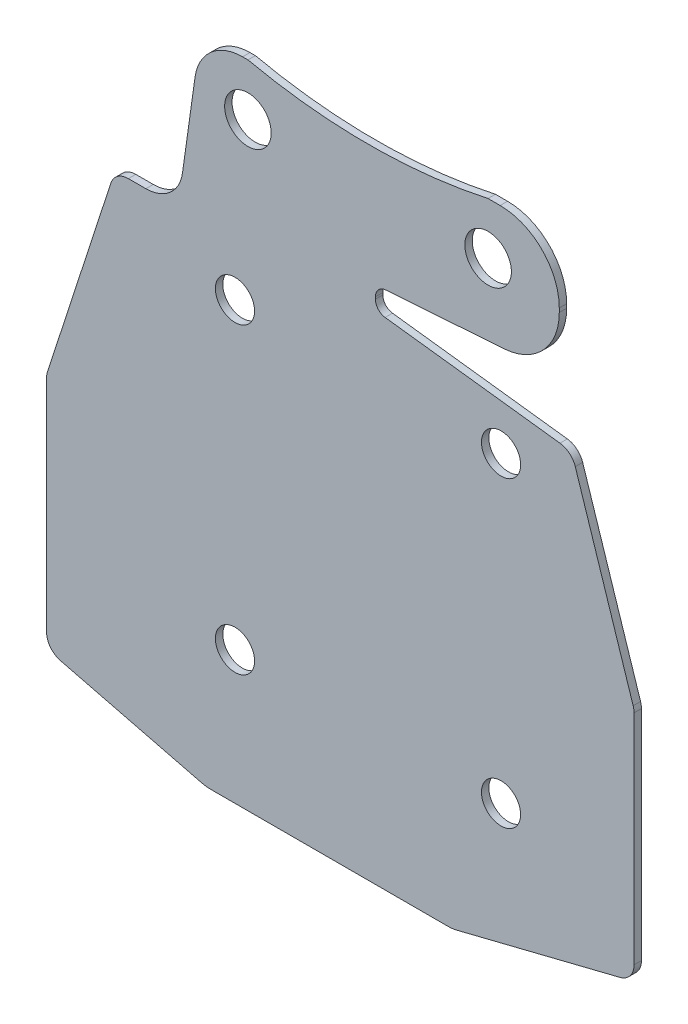
SolidWorks part; units mm, degrees
ref_plane "Plano frontal" through (0, 0, 0) normal (0, 0, 1) x (1, 0, 0)
ref_plane "Plano superior" through (0, 0, 0) normal (0, 1, 0) x (1, 0, 0)
ref_plane "Plano direito" through (0, 0, 0) normal (1, 0, 0) x (0, 0, -1)
sketch "Esboço1" plane through (0, 0, 0) normal (0, 0, 1) x (1, 0, 0)
  line L0 (-28.901, -44.5642) -> (-50.4937, -39.1805)
  line L1 (-50.4937, -39.1805) -> (-50.4937, -7.0642)
  line L2 (-50.4937, -7.0642) -> (-41.2335, 21.4358)
  line L3 (-41.2335, 21.4358) -> (-32.7051, 21.4358)
  line L4 (-32.7051, 21.4358) -> (-29.6132, 43.4358)
  line L5 (-29.6132, 43.4358) -> (18.8868, 43.4358)
  line L6 (18.8868, 43.4358) -> (18.8868, 27.4358)
  line L7 (18.8868, 27.4358) -> (-5.9937, 25.696)
  line L8 (-5.9937, 25.696) -> (-5.9937, 22.696)
  line L9 (-5.9937, 22.696) -> (20.5584, 19.4358)
  line L10 (20.5584, 19.4358) -> (29.0063, -6.5642)
  line L11 (29.0063, -6.5642) -> (29.0063, -38.4375)
  line L12 (29.0063, -38.4375) -> (4.4333, -44.5642)
  line L13 (4.4333, -44.5642) -> (-28.901, -44.5642)
  dimension "D1" = 14
  dimension "D2" = 14
  dimension "D3" = 79.5
  dimension "D4" = 18
  dimension "D5" = 18
  dimension "D6" = 8
  dimension "D7" = 66
  dimension "D8" = 37.5
  dimension "D9" = 22
  dimension "D10" = 11
  dimension "D11" = 4
  dimension "D12" = 24
  dimension "D13" = 48.5
  dimension "D14" = 38
  dimension "D15" = 35
  dimension "D16" = 16
  dimension "D17" = 3
extrude "Ressalto-extrusão1" add sketch "Esboço1" along normal blind 1
fillet "Filete1" radius 5 1 edges at (-32.7051, 21.4358, 0.5)
fillet "Filete2" radius 6.5 1 edges at (-29.6132, 43.4358, 0.5)
fillet "Filete3" radius 8 2 edges at (18.8868, 27.4358, 0.5) (18.8868, 43.4358, 0.5)
fillet "Filete4" radius 1.5 2 edges at (-5.9937, 22.696, 0.5) (-5.9937, 25.696, 0.5)
fillet "Filete5" radius 2.5 1 edges at (20.5584, 19.4358, 0.5)
fillet "Filete6" radius 2.5 1 edges at (29.0063, -6.5642, 0.5)
fillet "Filete7" radius 2.5 1 edges at (29.0063, -38.4375, 0.5)
fillet "Filete9" radius 5 2 edges at (4.4333, -44.5642, 0.5) (-28.901, -44.5642, 0.5)
fillet "Filete10" radius 2.5 2 edges at (-50.4937, -7.0642, 0.5) (-50.4937, -39.1805, 0.5)
fillet "Filete11" radius 2.5 1 edges at (-41.2335, 21.4358, 0.5)
sketch "Esboço2" plane through (0, 0, 1) normal (0, 0, 1) x (1, 0, 0)
  line L0 (29.0063, -21.7222) -> (11.0063, -21.7222) construction
  line L1 (29.0063, -36.4843) -> (29.0063, -6.9602) construction
  line L2 (-24.9937, -26.5642) -> (-24.9937, 14.4358) construction
  line L4 (11.0063, -37.2324) -> (11.0063, 21.3947) construction
  line L5 (-24.9937, 14.4358) -> (11.0063, 14.4358) construction
  line L6 (11.0063, -26.5642) -> (-24.9937, -26.5642) construction
  line L7 (-24.9937, 14.4358) -> (-24.9937, 36.4358) construction
  line L8 (-24.9937, 36.4358) -> (-23.2437, 36.4358) construction
  line L9 (-23.2437, 36.4358) -> (9.2563, 36.4358) construction
  circle A0 centre (-24.9937, -26.5642) radius 2.65
  circle A1 centre (11.0063, -26.5642) radius 2.65
  circle A2 centre (-24.9937, 14.4358) radius 2.65
  circle A3 centre (11.0063, 14.4358) radius 2.65
  circle A4 centre (-23.2437, 36.4358) radius 3.15
  circle A5 centre (9.2563, 36.4358) radius 3.15
  dimension "D2" = 5.3
  dimension "D4" = 5.3
  dimension "D5" = 5.3
  dimension "D6" = 5.3
  dimension "D9" = 6.3
  dimension "D11" = 6.3
  dimension "D1" = 18
  dimension "D3" = 36
  dimension "D7" = 22
  dimension "D8" = 1.75
  dimension "D10" = 32.5
extrude "Corte-extrusão1" cut sketch "Esboço2" against normal blind 1
sketch "Esboço3" plane through (0, 0, 1) normal (0, 0, 1) x (1, 0, 0)
  line L0 (-23.2437, 36.4358) -> (9.2563, 36.4358) construction
  line L2 (10.8868, 43.4358) -> (-23.9629, 43.4358) construction
  line L3 (-6.9937, 43.4358) -> (-6.9937, 41.6858) construction
  circle A0 centre (-6.9937, 117.9358) radius 76.25
  dimension "D1" = 1.75
extrude "Corte-extrusão2" cut sketch "Esboço3" against normal blind 1
